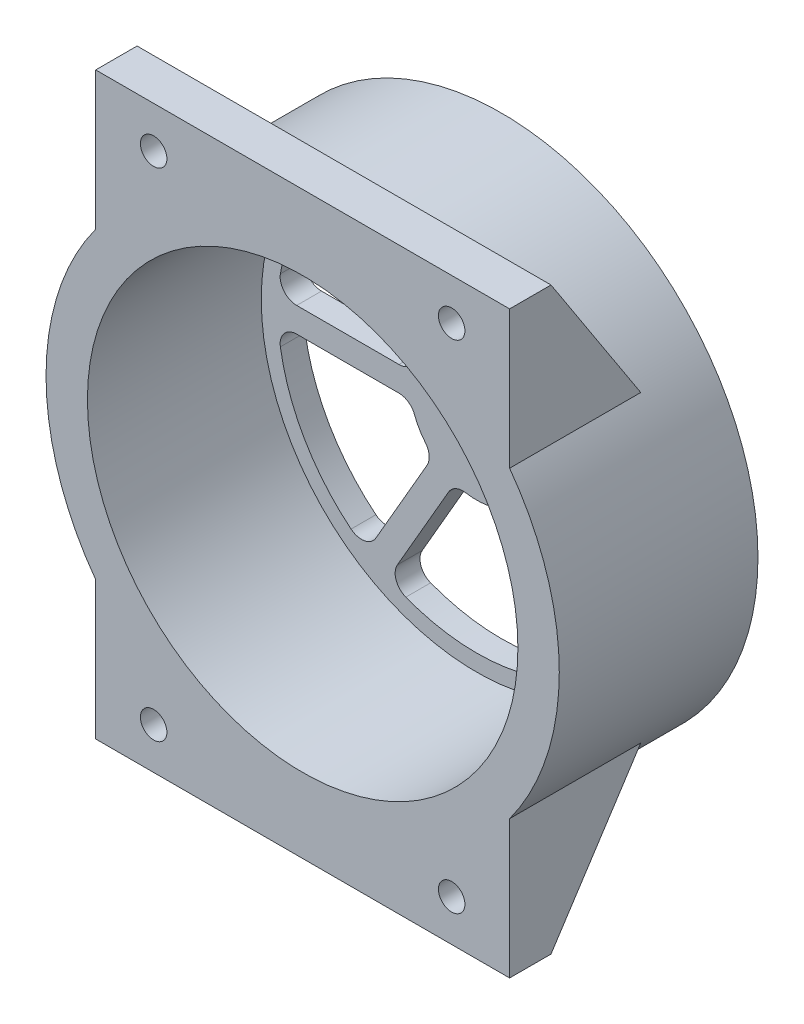
SolidWorks part; units mm, degrees
ref_plane "Front Plane" through (0, 0, 0) normal (0, 0, 1) x (1, 0, 0)
ref_plane "Top Plane" through (0, 0, 0) normal (0, 1, 0) x (1, 0, 0)
ref_plane "Right Plane" through (0, 0, 0) normal (1, 0, 0) x (0, 0, -1)
sketch "Sketch1" plane through (0, 0, 0) normal (1, 0, 0) x (0, 0, -1)
  line L0 (0, 0) -> (-41.7222, 0) construction
  line L1 (0, 0) -> (0, 31)
  line L3 (-24, 31) -> (-24, 26)
  line L4 (-24, 26) -> (-3, 26)
  line L5 (-3, 26) -> (-3, 0)
  line L6 (-3, 0) -> (0, 0)
  line L9 (-24, 31) -> (0, 31)
  dimension "D1" = 52
  dimension "D2" = 3
  dimension "D4" = 21
  dimension "D6" = 5
revolve "Revolve1" add sketch "Sketch1" angle 360 about L0
sketch "Sketch2" plane through (0, 0, 24) normal (0, 0, 1) x (1, 0, 0)
  line L0 (0, 0) -> (43.422, 0) construction
  line L1 (25, 35) -> (-25, 35)
  line L2 (-25, 35) -> (-25, 18.3303)
  line L3 (25, 35) -> (25, 18.3303)
  line L4 (25, -35) -> (25, -18.3303)
  line L5 (-25, -35) -> (-25, -18.3303)
  line L6 (25, -35) -> (-25, -35)
  circle A0 centre (0, 0) radius 31 construction
  arc A1 (-25, -18.3303) -> (25, -18.3303) centre (0, 0) ccw
  arc A2 (25, 18.3303) -> (-25, 18.3303) centre (0, 0) ccw
  point P6 (0, 35)
  dimension "D1" = 50
  dimension "D2" = 35
extrude "Boss-Extrude1" add sketch "Sketch2" against normal blind 5
sketch "Sketch3" plane through (25, 0, 0) normal (1, 0, 0) x (0, 0, -1)
  line L0 (-19, 35) -> (-8.1592, 18.3303)
  line L1 (-8.1592, 18.3303) -> (-19, 18.3303) construction
rib "Rib4" sketch "Sketch3" sketch "Sketch3" thickness 2 extrusion direction parallel to sketch draft on no parameters "D1"=2
mirror "Mirror1" about plane through (0, 0, 0) normal (0, 1, 0) of "Rib4"
mirror "Mirror2" about plane through (0, 0, 0) normal (1, 0, 0) of "Mirror1", "Rib4"
sketch "Sketch4" plane through (0, 0, 3) normal (0, 0, 1) x (1, 0, 0)
  line L0 (-9.5609, 19.5599) -> (-3.3847, 8.8625)
  line L1 (9.5609, 19.5599) -> (3.3847, 8.8625)
  line L2 (21.7198, 1.5) -> (9.3675, 1.5)
  line L3 (12.1589, 18.0599) -> (5.9828, 7.3625)
  line L4 (12.1589, -18.0599) -> (5.9828, -7.3625)
  line L5 (21.7198, -1.5) -> (9.3675, -1.5)
  line L6 (-9.5609, -19.5599) -> (-3.3847, -8.8625)
  line L7 (9.5609, -19.5599) -> (3.3847, -8.8625)
  line L8 (-21.7198, -1.5) -> (-9.3675, -1.5)
  line L9 (-12.1589, -18.0599) -> (-5.9828, -7.3625)
  line L10 (-12.1589, 18.0599) -> (-5.9828, 7.3625)
  line L11 (-21.7198, 1.5) -> (-9.3675, 1.5)
  arc A0 (-8.5405, 22.429) -> (8.5405, 22.429) centre (0, 0) cw
  arc A1 (1.3221, 7.89) -> (-1.3221, 7.89) centre (0, 0) ccw
  arc A2 (1.3221, 7.89) -> (3.3847, 8.8625) centre (1.6527, 9.8625) ccw
  arc A3 (-1.3221, 7.89) -> (-3.3847, 8.8625) centre (-1.6527, 9.8625) cw
  arc A4 (9.5609, 19.5599) -> (8.5405, 22.429) centre (7.8288, 20.5599) ccw
  arc A5 (-8.5405, 22.429) -> (-9.5609, 19.5599) centre (-7.8288, 20.5599) ccw
  arc A6 (21.7198, 1.5) -> (23.6943, 3.8182) centre (21.7198, 3.5) ccw
  arc A7 (7.494, 2.8) -> (9.3675, 1.5) centre (9.3675, 3.5) ccw
  arc A8 (7.494, 2.8) -> (6.1719, 5.09) centre (0, 0) ccw
  arc A9 (6.1719, 5.09) -> (5.9828, 7.3625) centre (7.7148, 6.3625) cw
  arc A10 (15.1538, 18.6108) -> (12.1589, 18.0599) centre (13.891, 17.0599) ccw
  arc A11 (15.1538, 18.6108) -> (23.6943, 3.8182) centre (0, 0) cw
  arc A12 (12.1589, -18.0599) -> (15.1538, -18.6108) centre (13.891, -17.0599) ccw
  arc A13 (6.1719, -5.09) -> (5.9828, -7.3625) centre (7.7148, -6.3625) ccw
  arc A14 (6.1719, -5.09) -> (7.494, -2.8) centre (0, 0) ccw
  arc A15 (7.494, -2.8) -> (9.3675, -1.5) centre (9.3675, -3.5) cw
  arc A16 (23.6943, -3.8182) -> (21.7198, -1.5) centre (21.7198, -3.5) ccw
  arc A17 (23.6943, -3.8182) -> (15.1538, -18.6108) centre (0, 0) cw
  arc A18 (-9.5609, -19.5599) -> (-8.5405, -22.429) centre (-7.8288, -20.5599) ccw
  arc A19 (-1.3221, -7.89) -> (-3.3847, -8.8625) centre (-1.6527, -9.8625) ccw
  arc A20 (-1.3221, -7.89) -> (1.3221, -7.89) centre (0, 0) ccw
  arc A21 (1.3221, -7.89) -> (3.3847, -8.8625) centre (1.6527, -9.8625) cw
  arc A22 (8.5405, -22.429) -> (9.5609, -19.5599) centre (7.8288, -20.5599) ccw
  arc A23 (8.5405, -22.429) -> (-8.5405, -22.429) centre (0, 0) cw
  arc A24 (-21.7198, -1.5) -> (-23.6943, -3.8182) centre (-21.7198, -3.5) ccw
  arc A25 (-7.494, -2.8) -> (-9.3675, -1.5) centre (-9.3675, -3.5) ccw
  arc A26 (-7.494, -2.8) -> (-6.1719, -5.09) centre (0, 0) ccw
  arc A27 (-6.1719, -5.09) -> (-5.9828, -7.3625) centre (-7.7148, -6.3625) cw
  arc A28 (-15.1538, -18.6108) -> (-12.1589, -18.0599) centre (-13.891, -17.0599) ccw
  arc A29 (-15.1538, -18.6108) -> (-23.6943, -3.8182) centre (0, 0) cw
  arc A30 (-12.1589, 18.0599) -> (-15.1538, 18.6108) centre (-13.891, 17.0599) ccw
  arc A31 (-6.1719, 5.09) -> (-5.9828, 7.3625) centre (-7.7148, 6.3625) ccw
  arc A32 (-6.1719, 5.09) -> (-7.494, 2.8) centre (0, 0) ccw
  arc A33 (-7.494, 2.8) -> (-9.3675, 1.5) centre (-9.3675, 3.5) cw
  arc A34 (-23.6943, 3.8182) -> (-21.7198, 1.5) centre (-21.7198, 3.5) ccw
  arc A35 (-23.6943, 3.8182) -> (-15.1538, 18.6108) centre (0, 0) cw
  point P77 (0, 0)
  dimension "D1" = 2
  dimension "D4" = 8
  dimension "D5" = 24
  dimension "D3" = 3
  dimension "D2" = 6
extrude "Cut-Extrude1" cut sketch "Sketch4" against normal through all
sketch "Sketch5" plane through (0, 0, 24) normal (0, 0, 1) x (1, 0, 0)
  line L0 (0, 0) -> (58.4424, 0) construction
  line L1 (0, 0) -> (0, 40.4015) construction
  circle A0 centre (-18, 30) radius 1.6
  circle A1 centre (18, 30) radius 1.6
  circle A2 centre (18, -30) radius 1.6
  circle A3 centre (-18, -30) radius 1.6
  dimension "D1" = 3.2
  dimension "D2" = 18
  dimension "D3" = 30
extrude "Cut-Extrude2" cut sketch "Sketch5" against normal through all
sketch "Sketch6" plane through (0, 0, 19) normal (0, 0, -1) x (-1, 0, 0)
  circle A0 centre (0, -119.4991) radius 9
  dimension "D1" = 18
